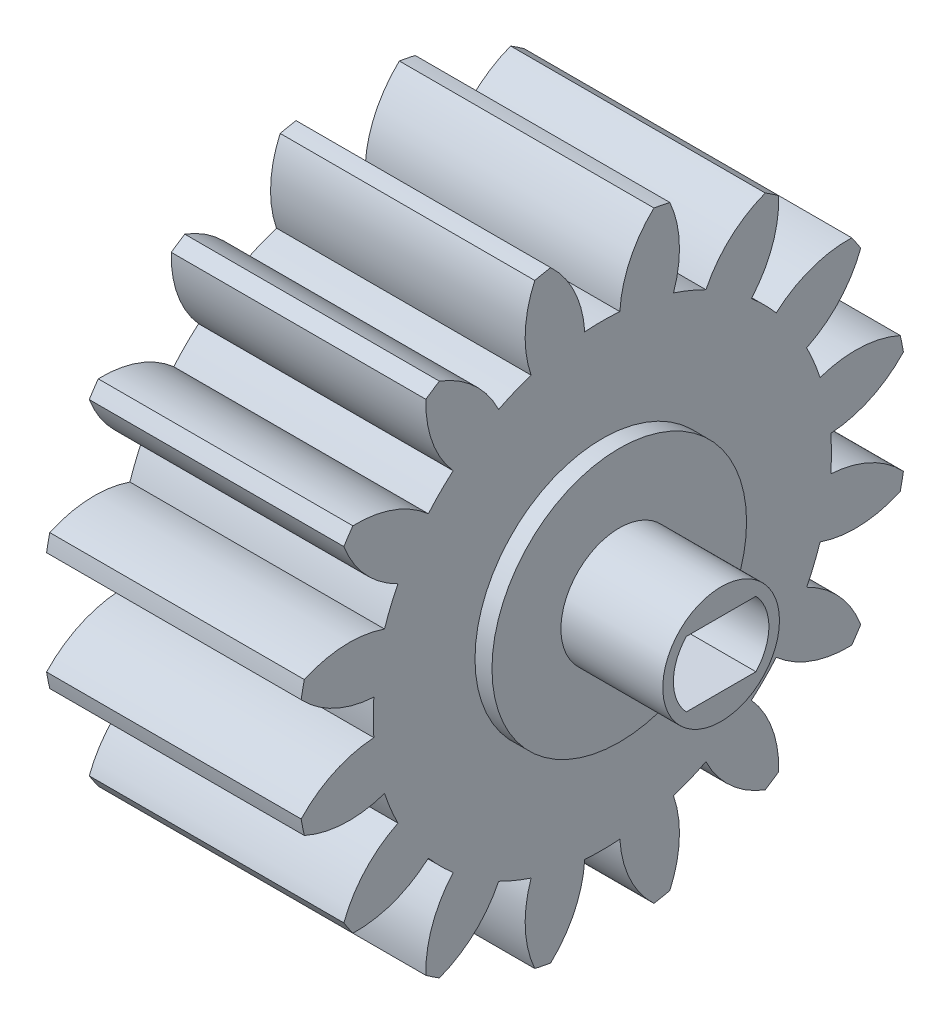
SolidWorks part; units mm, degrees
ref_plane "Plane1" through (0, 0, 0) normal (0, 0, 1) x (1, 0, 0)
ref_plane "Plane2" through (0, 0, 0) normal (0, 1, 0) x (1, 0, 0)
ref_plane "Plane3" through (0, 0, 0) normal (1, 0, 0) x (0, 0, -1)
other "Configuration Table"
sketch "HoldingSke" plane through (0, 0, 0) normal (0, 1, 0) x (1, 0, 0)
  line L0 (0, 0) -> (0.4806, -0.1378)
  line L1 (-15, 0) -> (100, 0) construction
  line L2 (0, 0) -> (-2.1039, 2.3779)
  line L3 (0, 0) -> (-11.863, 4.5341)
  line L4 (0, 0) -> (8.3015, 2.3804)
  line L5 (0, 0) -> (-42.1629, -15.7255)
  line L6 (0, 0) -> (-12.4344, -8.3896)
  line L7 (-2.1039, 2.3779) -> (7.5823, 46.3231)
  line L8 (-76.2, 54.61) -> (-75.3, 54.61)
  line L9 (-71.009, 38.7566) -> (-53.1078, 45.2721)
  line L10 (-76.2, 71.12) -> (104.1128, 71.12)
  line L11 (0, 0) -> (-15, 0)
  line L12 (-76.2, 101.6) -> (-76.133, 101.6)
  line L13 (24.9733, 27.94) -> (52.9518, 28.4284)
  line L14 (24.9733, 27.94) -> (24.9743, 27.94)
  line L15 (24.9733, 27.94) -> (100.4006, 29.5858)
  line L16 (-63.627, -2) -> (-12.827, -2)
  circle A0 centre (0, 0) radius 2.5
  circle A1 centre (0, 0) radius 5
  circle A2 centre (0, 0) radius 5
  circle A3 centre (0, 0) radius 2.5
  dimension "MHD" = 10
  dimension "Hub_dia" = 10
  dimension "Bore" = 5
  dimension "MBD" = 5
  dimension "Num_teeth" = 16
  dimension "Pitch" = 0.5
  dimension "Overall_len" = 45
  dimension "Show_teeth" = 16
  dimension "Thickness" = 15
  dimension "OAL" = 45.0001
  dimension "T_dim" = 0.9
  dimension "Ap" = 20
  dimension "H" = 19.05
  dimension "Pitch_radius" = 180.3128
  dimension "Width" = 15
  dimension "Backlash" = 0.067
  dimension "Addendum_fac" = 1
  dimension "Dedendum_fac" = 1.25
  dimension "Clearance_fac" = 0.25
  dimension "Dedendum_add" = 0.001
  dimension "Module" = 2
sketch "BasProSke" plane through (0, 0, 0) normal (0, 1, 0) x (1, 0, 0)
  line L0 (-10, 0) -> (60, 0) construction
  line L1 (0, 0) -> (0, 18)
  line L2 (0, 0) -> (15, 0)
  line L3 (15, 0) -> (15, 18)
  line L4 (15, 18) -> (0, 18)
  dimension "Thickness" = 15
  dimension "Diameter" = 36
revolve "Base-Revolve" add sketch "BasProSke" angle 360 about L0
sketch "TooCutSke" plane through (0, 0, 0) normal (1, 0, 0) x (0, 0, -1)
  line L1 (0, 0) -> (0, 107) construction
  line L2 (0, 0) -> (-1.6854, 15.911) construction
  line L3 (0, 0) -> (-6.2172, 31.2558) construction
  line L4 (-1.6854, 15.911) -> (-3.1086, 15.6279) construction
  arc A0 (1.0343, 13.4593) -> (-1.0343, 13.4593) centre (0, 0) ccw
  arc A1 (3.0657, 17.7628) -> (-3.0657, 17.7628) centre (0, 0) ccw
  circle A2 centre (0, 0) radius 16 construction
  circle A3 centre (0, 0) radius 15.0351 construction
  arc A4 (-1.0343, 13.4593) -> (-3.0657, 17.7628) centre (-7.4228, 13.075) ccw
  arc A5 (3.0657, 17.7628) -> (1.0343, 13.4593) centre (7.4228, 13.075) ccw
  dimension "Root_dia" = 26.998
  dimension "Overcut_dia" = 36.0508
  dimension "Pitch_dia" = 32
  dimension "Base_dia" = 30.0702
  dimension "Flank_rad" = 6.4
  dimension "Half_ang" = 11.25
  dimension "Half_CT" = 1.451
extrude "ToothCut" cut sketch "TooCutSke" along normal through all
fillet "Breaks" [suppressed] radius 0.04
fillet "RootFillets" [suppressed] radius 0.501
pattern_circular "TeethCuts" count 16 every 22.5 about axis through (-10, 0, 0) along (1, 0, 0) of "ToothCut", "RootFillets", "Breaks"
sketch "HubNeaOneSke" plane through (0, 0, 0) normal (-1, 0, 0) x (0, 0, 1)
  circle A0 centre (0, 0) radius 5
  dimension "Diameter" = 10
extrude "HubNearOne" [suppressed] add sketch "HubNeaOneSke" along normal blind 30.0001
sketch "HubNeaBotSke" plane through (0, 0, 0) normal (-1, 0, 0) x (0, 0, 1)
  circle A0 centre (0, 0) radius 5
  dimension "Diameter" = 10
extrude "HubNearBoth" add sketch "HubNeaBotSke" along normal blind 15
ref_plane "FarPln" through (15, 0, 0) normal (1, 0, 0) x (0, 0, -1)
sketch "HubFarSke" plane through (15, 0, 0) normal (1, 0, 0) x (0, 0, -1)
  circle A0 centre (0, 0) radius 5
  dimension "Diameter" = 10
extrude "HubFar" add sketch "HubFarSke" along normal blind 15
sketch "BorSke" plane through (0, 0, 0) normal (1, 0, 0) x (0, 0, -1)
  circle A0 centre (0, 0) radius 2.5
  dimension "Diameter" = 5
extrude "Bore" cut sketch "BorSke" along normal mid plane 90.0001
sketch "KeySke" plane through (0, 0, 0) normal (1, 0, 0) x (0, 0, -1)
  line L0 (-1, 0) -> (-1, 3.4)
  line L1 (-1, 3.4) -> (1, 3.4)
  line L2 (1, 3.4) -> (1, 0)
  line L3 (0, 0) -> (0, 34) construction
  line L4 (-1, 0) -> (1, 0)
  dimension "Offset" = 3.4
  dimension "Width" = 2
extrude "Keyway" [suppressed] cut sketch "KeySke" along normal mid plane 90.0001
pattern_circular "Keyway2" [suppressed] count 2 every 90 about axis through (-10, 0, 0) along (1, 0, 0)
sketch "Sketch3" plane through (-15, 0, 0) normal (-1, 0, 0) x (0, 0, 1)
  circle A1 centre (0, 0) radius 5
  circle A2 centre (0, 0) radius 5
  dimension "D1" = 0
extrude "Cut-Extrude1" cut sketch "Sketch3" against normal up to surface (15 mm away) up to face at (0, 0, -5)
sketch "Sketch5" plane through (0, 0, 0) normal (-1, 0, 0) x (0, 0, 1)
  circle A0 centre (0, 0) radius 2.5 construction
  circle A1 centre (0, 0) radius 2.5
extrude "Boss-Extrude1" add sketch "Sketch5" against normal blind 20
sketch "Sketch6" plane through (15, 0, 0) normal (1, 0, 0) x (0, 0, -1)
  circle A0 centre (0, 0) radius 5 construction
  circle A1 centre (0, 0) radius 5
  circle A2 centre (0, 0) radius 7.5
  dimension "D1" = 15
extrude "Boss-Extrude2" add sketch "Sketch6" along normal blind 1
sketch "Sketch7" plane through (16, 0, 0) normal (1, 0, 0) x (0, 0, -1)
  circle A0 centre (0, 0) radius 3.4375
  circle A1 centre (0, 0) radius 7.5
  dimension "D1" = 6.875
extrude "Cut-Extrude2" cut sketch "Sketch7" along normal through all contours A1 | A0
sketch "Sketch8" plane through (20, 0, 0) normal (1, 0, 0) x (0, 0, -1)
  circle A1 centre (0, 0) radius 2.5
  circle A2 centre (0, 0) radius 2.5
  dimension "D1" = 0
extrude "Boss-Extrude3" add sketch "Sketch8" along normal up to surface (10 mm away) up to face at (30, 0, -2.5)
sketch "Sketch10" plane through (30, 0, 0) normal (1, 0, 0) x (0, 0, -1)
  line L0 (-2.0505, 1.925) -> (2.0505, 1.925)
  line L1 (-2.0505, -1.925) -> (2.0505, -1.925)
  arc A0 (-2.0505, 1.925) -> (-2.0505, -1.925) centre (0, 0) ccw
  circle A1 centre (0, 0) radius 3.4375
  circle A2 centre (0, 0) radius 3.4375
  arc A3 (2.0505, -1.925) -> (2.0505, 1.925) centre (0, 0) ccw
  dimension "D2" = 5.625
  dimension "D3" = 3.85
  dimension "D1" = 0
extrude "Cut-Extrude3" cut sketch "Sketch10" against normal up to surface (14 mm away) flip side to cut up to face at (16, 0, -7.5)
sketch "Sketch12" plane through (30, 0, 0) normal (1, 0, 0) x (0, 0, -1)
  circle A1 centre (0, 0) radius 3.4375
  circle A2 centre (0, 0) radius 3.4375
  dimension "D1" = 0
extrude "Cut-Extrude4" cut sketch "Sketch12" against normal blind 8
equation "' \"Module@HoldingSke\" = 6.35"
equation "' \"Num_teeth@HoldingSke\" = 12"
equation "' \"Ap@HoldingSke\" =  20"
equation "' \"Ap@HoldingSke\" = 20"
equation "' \"Width@HoldingSke\" = 0.5 * 25.4"
equation "' \"Hub_dia@HoldingSke\"= 1 * 25.4"
equation "' \"Hub_dia@HoldingSke\" = 1 * 25.4"
equation "' \"Overall_len@HoldingSke\" = 1.0 * 25.4"
equation "' \"Bore@HoldingSke\" = 0.75 * 25.4"
equation "' \"T_dim@HoldingSke\" = 0.1 * 25.4"
equation "' \"Width@KeySke\" = 0.25 * 25.4"
equation "' \"Show_teeth@HoldingSke\" = 13"
equation "' \"Backlash@HoldingSke\" = 0.009 * 25.4"
equation "' \"Addendum_fac@HoldingSke\" = 1.0"
equation "' \"Dedendum_fac@HoldingSke\" = 1.25"
equation "' \"Dedendum_add@HoldingSke\" = 0.00005 * 25.4"
equation "' \"Clearance_fac@HoldingSke\" = 0.25"
equation "\"Pitch@HoldingSke\" = 1 / \"Module@HoldingSke\""
equation "\"Overcut_dia@TooCutSke\" = (\"Num_teeth@HoldingSke\" + 2 * \"Addendum_fac@HoldingSke\") / \"Pitch@HoldingSke\" + 0.002 * 25.4"
equation "\"Pitch_dia@TooCutSke\" = \"Num_teeth@HoldingSke\" / \"Pitch@HoldingSke\""
equation "\"Base_dia@TooCutSke\" = \"Num_teeth@HoldingSke\" / \"Pitch@HoldingSke\" * cos((\"Ap@HoldingSke\"  * 3.14159265 / 180))"
equation "\"Root_dia@TooCutSke\" = (\"Num_teeth@HoldingSke\" + 2) / \"Pitch@HoldingSke\" - 2 * (\"Addendum_fac@HoldingSke\" + \"Dedendum_fac@HoldingSke\") / \"Pitch@HoldingSke\" - \"Dedendum_add@HoldingSke\" * 2"
equation "\"Half_ang@TooCutSke\" = 180 / \"Num_teeth@HoldingSke\""
equation "\"Half_CT@TooCutSke\" = \"Num_teeth@HoldingSke\" / \"Pitch@HoldingSke\" * sin((3.14159265 / 2 / \"Num_teeth@HoldingSke\")) / 2 - 7 * \"Backlash@HoldingSke\" / 4"
equation "\"Flank_rad@TooCutSke\" = \"Num_teeth@HoldingSke\" / \"Pitch@HoldingSke\" / 5"
equation "\"Radius@RootFillets\" = \"Clearance_fac@HoldingSke\" / \"Pitch@HoldingSke\" + \"Dedendum_add@HoldingSke\""
equation "\"Break_rad@Breaks\" = 0.02 / \"Pitch@HoldingSke\""
equation "\"Thickness@HoldingSke\" = \"Width@HoldingSke\""
equation "\"OAL@HoldingSke\" = \"Thickness@HoldingSke\""
equation "\"MHD@HoldingSke\" = (\"Num_teeth@HoldingSke\" + 2) / \"Pitch@HoldingSke\" - 2 * (\"Addendum_fac@HoldingSke\" + \"Dedendum_fac@HoldingSke\")  / \"Pitch@HoldingSke\" - \"Dedendum_add@HoldingSke\" * 2"
equation "\"MBD@HoldingSke\" = (\"Num_teeth@HoldingSke\" + 2) / \"Pitch@HoldingSke\" - 2 * (\"Addendum_fac@HoldingSke\" + \"Dedendum_fac@HoldingSke\")  / \"Pitch@HoldingSke\" - \"Dedendum_add@HoldingSke\" * 2 - 0.002 * 25.4"
equation "\"MHD@HoldingSke\" = ((sgn( \"MHD@HoldingSke\" - \"Hub_dia@HoldingSke\" )-1)*( \"MHD@HoldingSke\" - \"Hub_dia@HoldingSke\" ))/-2+ \"Hub_dia@HoldingSke\""
equation "\"MBD@HoldingSke\" = ((sgn( \"MBD@HoldingSke\" - \"Bore@HoldingSke\" )-1)*( \"MBD@HoldingSke\" - \"Bore@HoldingSke\" ))/-2+ \"Bore@HoldingSke\""
equation "\"OAL@HoldingSke\" = ((sgn( \"OAL@HoldingSke\" - \"Overall_len@HoldingSke\" )+1)*( \"OAL@HoldingSke\" - \"Overall_len@HoldingSke\" ))/2 + \"Overall_len@HoldingSke\" + 0.000002 * 25.4"
equation "\"Num_teeth@TeethCuts\" = int( \"Show_teeth@HoldingSke\" ) + 1"
equation "\"Num_teeth@TeethCuts\" = ((sgn( \"Num_teeth@TeethCuts\" - \"Num_teeth@HoldingSke\" )-1)*( \"Num_teeth@TeethCuts\" - \"Num_teeth@HoldingSke\" ))/-2+ \"Num_teeth@HoldingSke\""
equation "\"Num_teeth@TeethCuts\" = ((sgn( \"Num_teeth@TeethCuts\" - 2.0)+1)*( \"Num_teeth@TeethCuts\" - 2.0))/2 +2.0"
equation "\"Angle@TeethCuts\" = 360.0 / \"Num_teeth@HoldingSke\""
equation "\"Diameter@BasProSke\" = (\"Num_teeth@HoldingSke\" + 2 * \"Addendum_fac@HoldingSke\") / \"Pitch@HoldingSke\""
equation "\"Thickness@BasProSke\"  = \"Thickness@HoldingSke\""
equation "' \"Fillet_rad@BasProSke\" =  \"Thickness@HoldingSke\" * 0.05"
equation "' \"Fillet_rad@BasProSke\" = \"Thickness@HoldingSke\" * 0.05"
equation "\"MHD@HoldingSke\" = ((sgn( \"MHD@HoldingSke\" - \"Root_dia@TooCutSke\" )-1)*( \"MHD@HoldingSke\" - \"Root_dia@TooCutSke\" ))/-2+ \"Root_dia@TooCutSke\""
equation "\"Diameter@HubNeaOneSke\" = \"MHD@HoldingSke\""
equation "\"Length@HubNearOne\" = \"OAL@HoldingSke\" - \"Thickness@BasProSke\""
equation "\"Diameter@HubNeaBotSke\" = \"MHD@HoldingSke\""
equation "\"Length@HubNearBoth\" = ( \"OAL@HoldingSke\" - \"Thickness@BasProSke\" ) / 2.0"
equation "\"Thickness@FarPln\" = \"Thickness@BasProSke\""
equation "\"Diameter@HubFarSke\" = \"MHD@HoldingSke\""
equation "\"Length@HubFar\" = ( \"OAL@HoldingSke\" - \"Thickness@BasProSke\" ) / 2.0"
equation "\"Diameter@BorSke\" = \"MBD@HoldingSke\""
equation "\"D1@Bore\" = \"OAL@HoldingSke\" * 2.0"
equation "\"D1@Keyway\" = \"OAL@HoldingSke\" * 2.0"
equation "\"Offset@KeySke\" = \"T_dim@HoldingSke\" + \"MBD@HoldingSke\" / 2.0"
